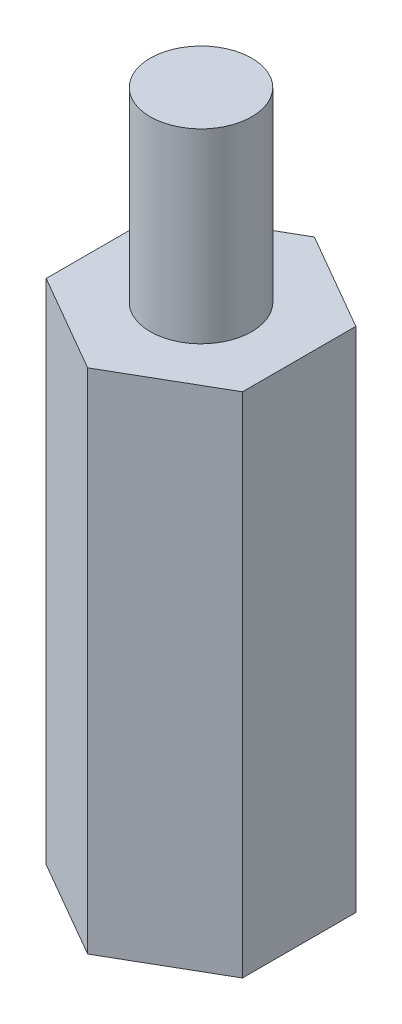
SolidWorks part; units mm, degrees
ref_plane "Front Plane" through (0, 0, 0) normal (0, 0, 1) x (1, 0, 0)
ref_plane "Top Plane" through (0, 0, 0) normal (0, 1, 0) x (1, 0, 0)
ref_plane "Right Plane" through (0, 0, 0) normal (1, 0, 0) x (0, 0, -1)
sketch "Sketch1" plane through (0, 0, 0) normal (0, 1, 0) x (1, 0, 0)
  line L1 (0, -3.3486) -> (2.9, -1.6743)
  line L2 (2.9, -1.6743) -> (2.9, 1.6743)
  line L3 (2.9, 1.6743) -> (0, 3.3486)
  line L4 (0, 3.3486) -> (-2.9, 1.6743)
  line L5 (-2.9, 1.6743) -> (-2.9, -1.6743)
  line L6 (-2.9, -1.6743) -> (0, -3.3486)
  circle A0 centre (0, 0) radius 2.9 construction
  circle A1 centre (0, 0) radius 1.5
  dimension "D2" = 3
  dimension "D1" = 5.8
extrude "Boss-Extrude1" add sketch "Sketch1" along normal mid plane 15
sketch "Sketch2" plane through (0, 7.5, 0) normal (0, 1, 0) x (1, 0, 0)
  circle A0 centre (0, 0) radius 1.5 construction
  circle A1 centre (0, 0) radius 1.5
extrude "Boss-Extrude2" add sketch "Sketch2" along normal blind 5.5 separate body
